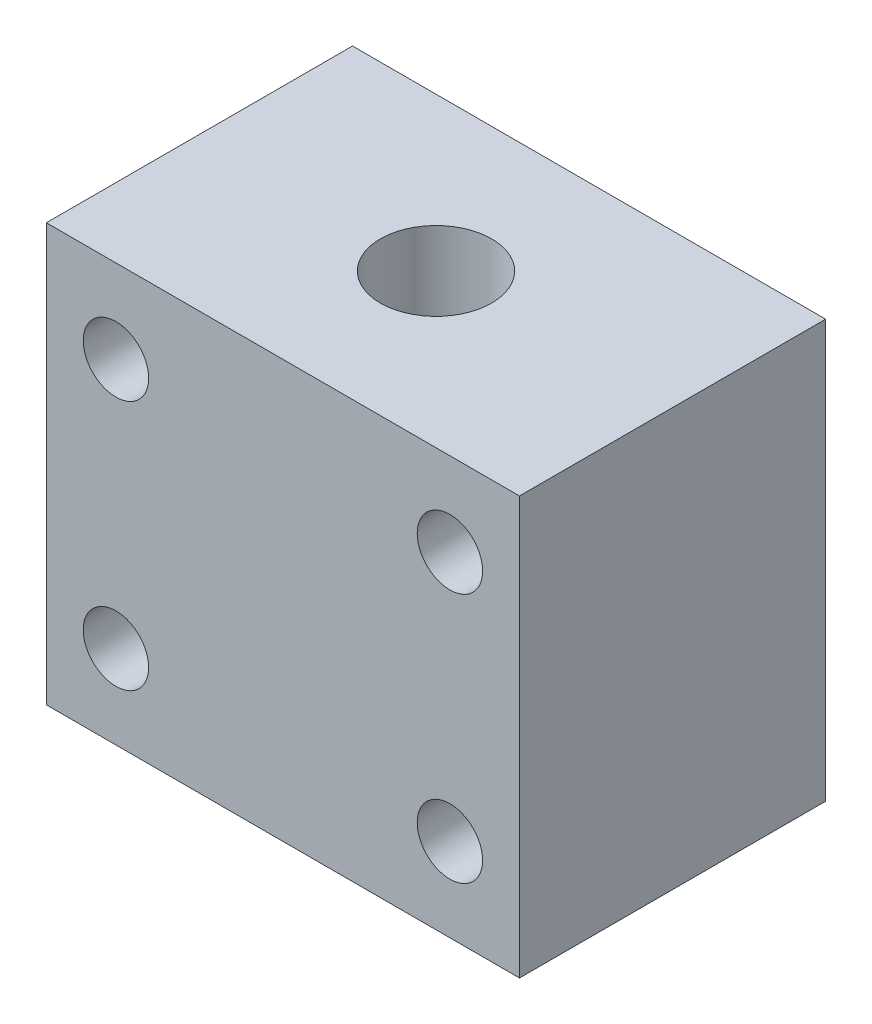
SolidWorks part; units mm, degrees
ref_plane "Front Plane" through (0, 0, 0) normal (0, 0, 1) x (1, 0, 0)
ref_plane "Top Plane" through (0, 0, 0) normal (0, 1, 0) x (1, 0, 0)
ref_plane "Right Plane" through (0, 0, 0) normal (1, 0, 0) x (0, 0, -1)
sketch "Sketch1" plane through (0, 0, 0) normal (0, 1, 0) x (1, 0, 0)
  line L1 (-17, 11) -> (17, 11)
  line L2 (-17, 11) -> (-17, -11)
  line L3 (-17, -11) -> (17, -11)
  line L4 (17, 11) -> (17, -11)
  line L5 (-17, 11) -> (17, -11) construction
  line L6 (-17, -11) -> (17, 11) construction
  circle A0 centre (0, 0) radius 4
  point P0 (0, 0)
extrude "Boss-Extrude1" add sketch "Sketch1" along normal blind 30
sketch "Sketch3" plane through (0, 0, 11) normal (0, 0, 1) x (1, 0, 0)
  circle A0 centre (-12, 24) radius 2.35
  circle A1 centre (-12, 6) radius 2.35
  circle A2 centre (12, 6) radius 2.35
  circle A3 centre (12, 24) radius 2.35
extrude "Cut-Extrude1" cut sketch "Sketch3" against normal blind 5
